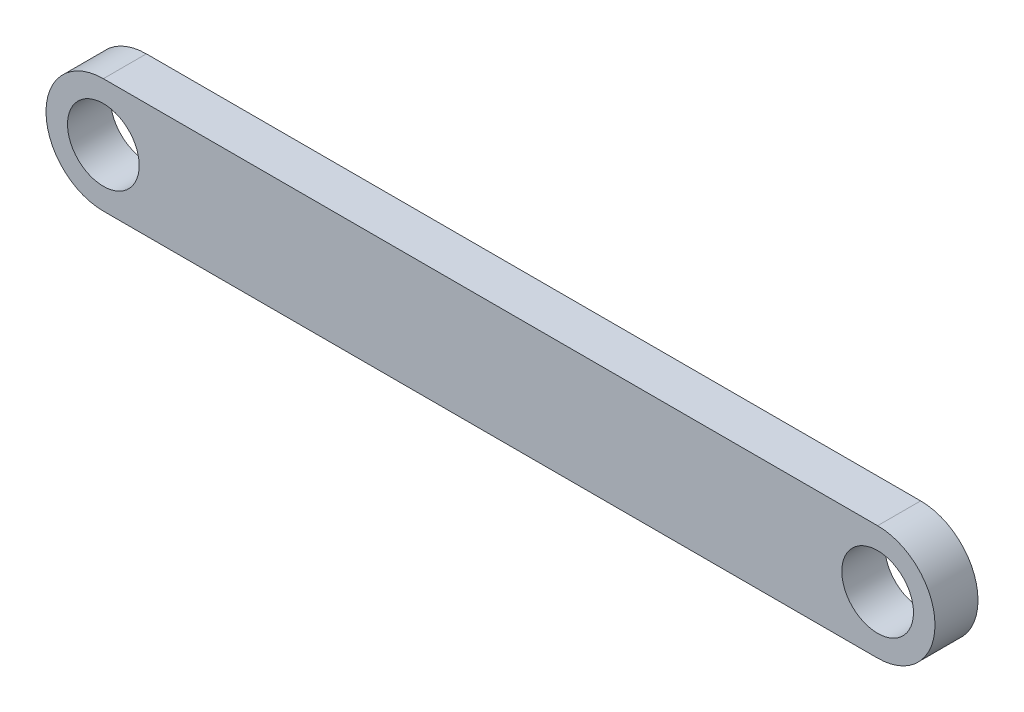
SolidWorks part; units mm, degrees
material "ABS"
ref_plane "Front Plane" through (0, 0, 0) normal (0, 0, 1) x (1, 0, 0)
ref_plane "Top Plane" through (0, 0, 0) normal (0, 1, 0) x (1, 0, 0)
ref_plane "Right Plane" through (0, 0, 0) normal (1, 0, 0) x (0, 0, -1)
sketch "Sketch1" plane through (0, 0, 0) normal (0, 0, 1) x (1, 0, 0)
  line L0 (0, 0) -> (-54, 0)
  dimension "D1" = 54
sketch "Sketch2" plane through (0, 0, 0) normal (0, 0, 1) x (1, 0, 0)
  line L0 (-54, 4) -> (0, 4)
  line L1 (-54, -4) -> (0, -4)
  circle A0 centre (-54, 0) radius 2.5
  circle A1 centre (0, 0) radius 2.5
  arc A2 (-54, 4) -> (-54, -4) centre (-54, 0) ccw
  arc A3 (0, -4) -> (0, 4) centre (0, 0) ccw
  dimension "D1" = 5
  dimension "D2" = 8
  dimension "D3" = 5
  dimension "D4" = 8
extrude "Boss-Extrude1" add sketch "Sketch2" along normal blind 3
